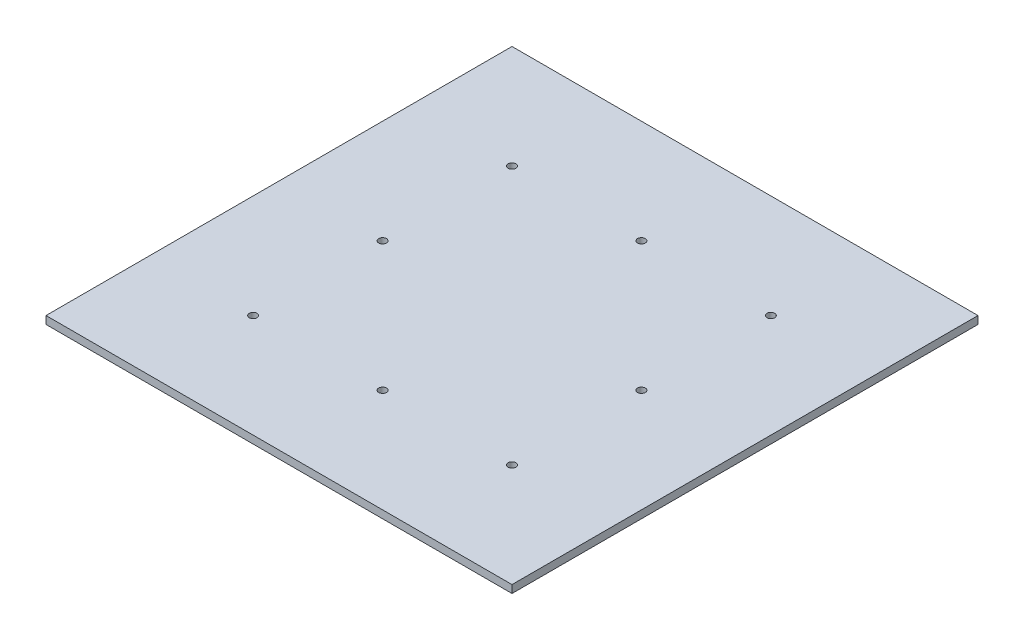
SolidWorks part; units mm, degrees
ref_plane "Front Plane" through (0, 0, 0) normal (0, 0, 1) x (1, 0, 0)
ref_plane "Top Plane" through (0, 0, 0) normal (0, 1, 0) x (1, 0, 0)
ref_plane "Right Plane" through (0, 0, 0) normal (1, 0, 0) x (0, 0, -1)
sketch "Sketch1" plane through (0, 0, 0) normal (0, 1, 0) x (1, 0, 0)
  line L1 (0, 0) -> (180, 0)
  line L2 (0, 0) -> (0, -180)
  line L3 (0, -180) -> (180, -180)
  line L4 (180, 0) -> (180, -180)
  dimension "D1" = 180
extrude "Boss-Extrude1" add sketch "Sketch1" along normal blind 3
sketch "Sketch2" plane through (0, 3, 0) normal (0, 1, 0) x (1, 0, 0)
  line L4 (0, 0) -> (0, -180) construction
  line L5 (180, 0) -> (0, 0) construction
  line L6 (180, -180) -> (180, 0) construction
  line L7 (0, -180) -> (180, -180) construction
  circle A0 centre (40, -40) radius 1.5
  circle A1 centre (140, -40) radius 1.5
  circle A2 centre (140, -140) radius 1.5
  circle A3 centre (40, -140) radius 1.5
  circle A4 centre (90, -40) radius 1.5
  circle A5 centre (140, -90) radius 1.5
  circle A6 centre (90, -140) radius 1.5
  circle A7 centre (40, -90) radius 1.5
  point P24 (0, 0)
  dimension "D1" = 40
  dimension "D2" = 40
  dimension "D3" = 40
  dimension "D4" = 40
  dimension "D5" = 40
  dimension "D6" = 50
  dimension "D7" = 50
  dimension "D8" = 40
  dimension "D9" = 40
  dimension "D10" = 50
  dimension "D11" = 50
  dimension "D12" = 40
extrude "Cut-Extrude1" cut sketch "Sketch2" against normal blind 3
